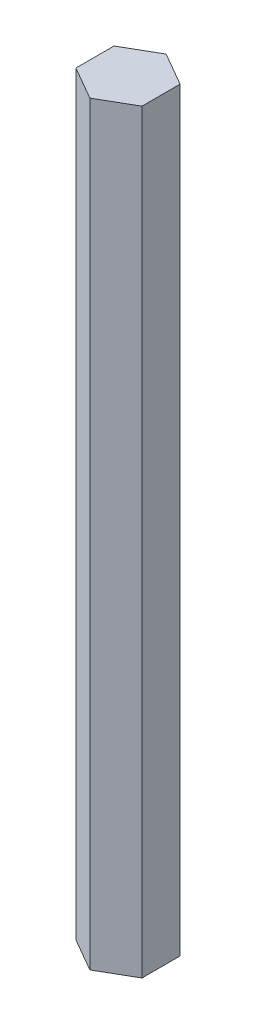
SolidWorks part; units mm, degrees
ref_plane "Front Plane" through (0, 0, 0) normal (0, 0, 1) x (1, 0, 0)
ref_plane "Top Plane" through (0, 0, 0) normal (0, 1, 0) x (1, 0, 0)
ref_plane "Right Plane" through (0, 0, 0) normal (1, 0, 0) x (0, 0, -1)
sketch "Sketch1" plane through (0, 0, 0) normal (0, 1, 0) x (1, 0, 0)
  line L1 (-1.323, 7.4242) -> (-5.768, 4.8579)
  line L2 (-5.768, 4.8579) -> (-5.768, -0.2748)
  line L3 (-5.768, -0.2748) -> (-1.323, -2.8411)
  line L4 (-1.323, -2.8411) -> (3.122, -0.2748)
  line L5 (3.122, -0.2748) -> (3.122, 4.8579)
  line L6 (3.122, 4.8579) -> (-1.323, 7.4242)
  circle A0 centre (-1.323, 2.2915) radius 4.445 construction
  point P11 (0, 0)
  point P13 (-1.323, 2.2915)
  dimension "D1" = 8.89
extrude "Boss-Extrude1" add sketch "Sketch1" along normal blind 101.6
